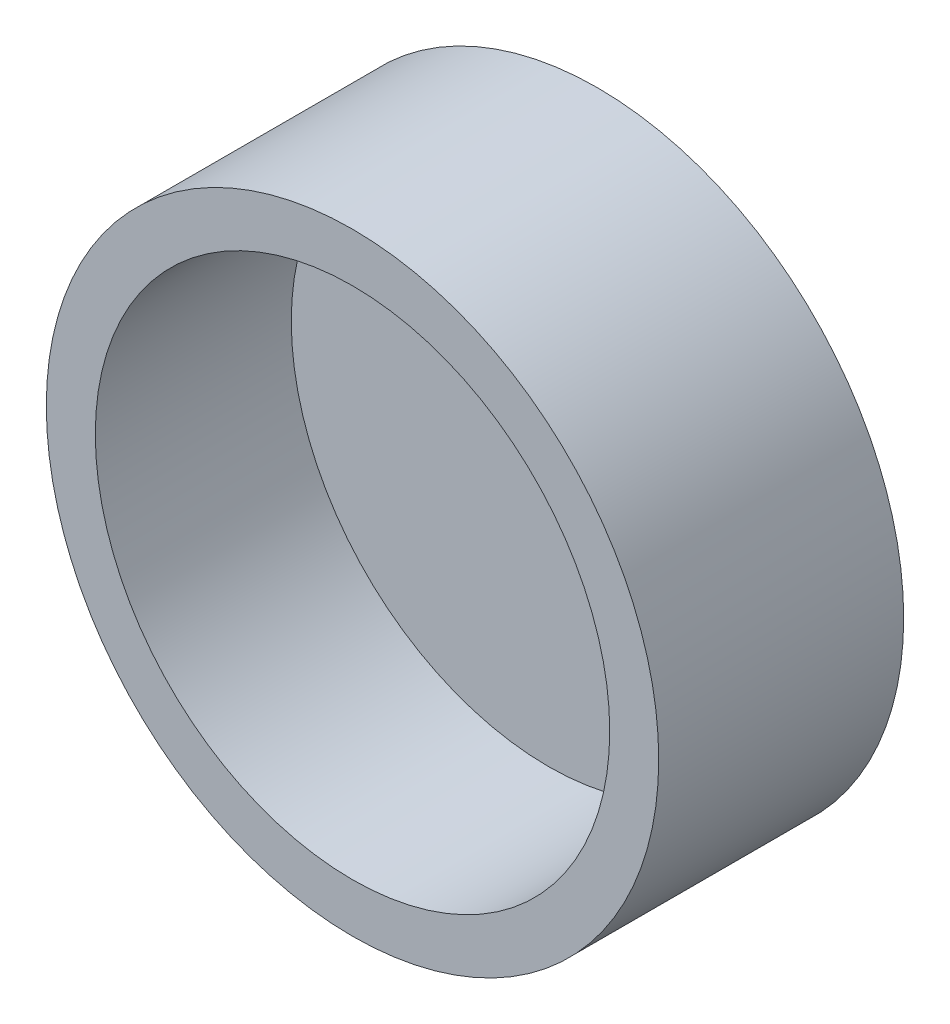
SolidWorks part; units mm, degrees
material "Plain Carbon Steel"
ref_plane "Front Plane" through (0, 0, 0) normal (0, 0, 1) x (1, 0, 0)
ref_plane "Top Plane" through (0, 0, 0) normal (0, 1, 0) x (1, 0, 0)
ref_plane "Right Plane" through (0, 0, 0) normal (1, 0, 0) x (0, 0, -1)
sketch "Sketch1" plane through (0, 0, 0) normal (0, 0, 1) x (1, 0, 0)
  circle A0 centre (0, 0) radius 15.875
  dimension "D1" = 31.75
extrude "Boss-Extrude1" add sketch "Sketch1" along normal blind 12.7
shell "Shell1" thickness 2.54
